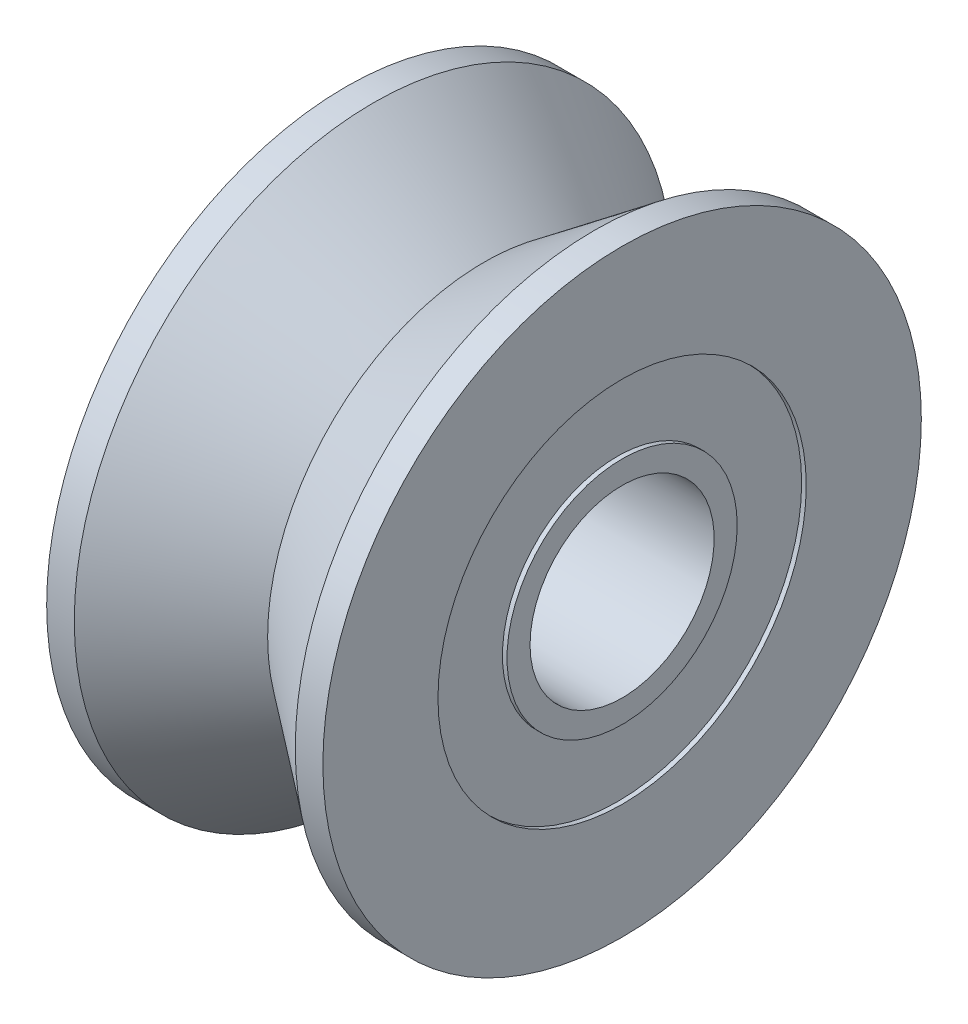
SolidWorks part; units mm, degrees
ref_plane "Front Plane" through (0, 0, 0) normal (0, 0, 1) x (1, 0, 0)
ref_plane "Top Plane" through (0, 0, 0) normal (0, 1, 0) x (1, 0, 0)
ref_plane "Right Plane" through (0, 0, 0) normal (1, 0, 0) x (0, 0, -1)
sketch "Sketch1" plane through (0, 0, 0) normal (0, 0, 1) x (1, 0, 0)
  line L0 (0, 0) -> (0, 13.2332) construction
  line L1 (0, 0) -> (10.1216, 0) construction
  line L2 (-3, 2) -> (3, 2)
  line L3 (3, 2) -> (3, 6.5)
  line L4 (3, 6.5) -> (2.4, 6.5)
  line L5 (2.4, 6.5) -> (0, 4.7)
  line L6 (-3, 2) -> (-3, 6.5)
  line L7 (-3, 6.5) -> (-2.4, 6.5)
  line L8 (-2.4, 6.5) -> (0, 4.7)
  point P9 (0, 2)
  dimension "D1" = 1.8
  dimension "D2" = 6
  dimension "D3" = 4
  dimension "D4" = 13
  dimension "D5" = 4.8
revolve "Revolve1" add sketch "Sketch1" angle 360 about L1
sketch "Sketch2" plane through (3, 0, 0) normal (1, 0, 0) x (0, 0, -1)
  circle A0 centre (0, 0) radius 2.5
  circle A1 centre (0, 0) radius 4
  circle A2 centre (0, 0) radius 2 construction
  dimension "D1" = 0.5
  dimension "D2" = 1.5
extrude "Cut-Extrude1" cut sketch "Sketch2" against normal blind 0.1
mirror "Mirror1" about plane through (0, 0, 0) normal (1, 0, 0) of "Cut-Extrude1"
